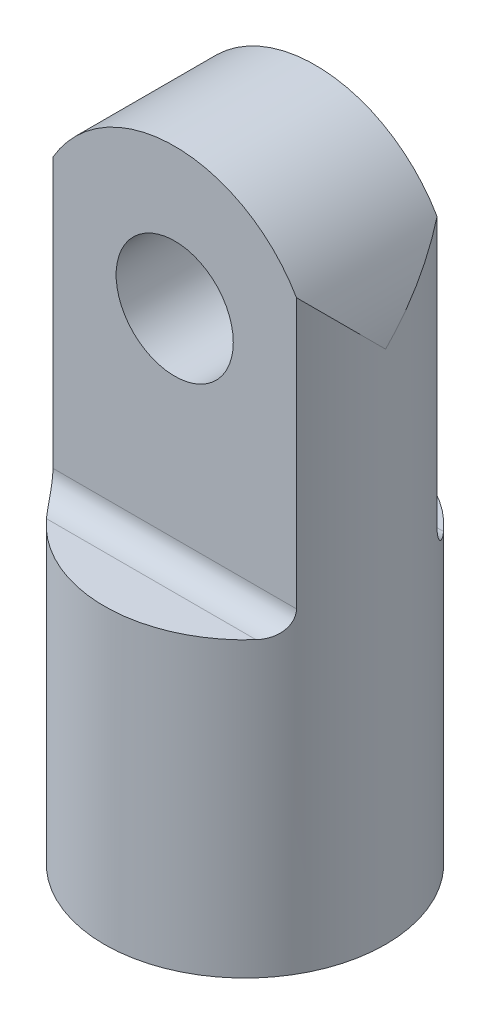
SolidWorks part; units mm, degrees
ref_plane "前视基准面" through (0, 0, 0) normal (0, 0, 1) x (1, 0, 0)
ref_plane "上视基准面" through (0, 0, 0) normal (0, 1, 0) x (1, 0, 0)
ref_plane "右视基准面" through (0, 0, 0) normal (1, 0, 0) x (0, 0, -1)
other "Configuration Table"
sketch "Sketch1" plane through (0, 0, 0) normal (0, 1, 0) x (1, 0, 0)
  circle A0 centre (0, 0) radius 6
  dimension "D1" = 12
extrude "Boss-Extrude1" add sketch "Sketch1" along normal blind 28
sketch "Sketch2" plane through (0, 28, 0) normal (0, 1, 0) x (1, 0, 0)
  line L0 (-7.8504, 0) -> (9.8739, 0) construction
  line L1 (-5.1962, 3) -> (5.1962, 3)
  line L2 (-5.1962, 3) -> (-5.1962, -3)
  line L3 (-5.1962, -3) -> (5.1962, -3)
  line L4 (5.1962, 3) -> (5.1962, -3)
  circle A0 centre (0, 0) radius 6 construction
  circle M6 centre (0, 0) radius 6
  dimension "D1" = 6
extrude "Cut-Extrude1" cut sketch "Sketch2" against normal blind 15.5 contours L1 M6 | L3 M6
sketch "Sketch3" plane through (0, 0, 3) normal (0, 0, 1) x (1, 0, 0)
  line L2 (-5.1962, 28) -> (5.1962, 28) construction
  line L3 (6, 0) -> (6, 28) construction
  line L4 (-6, 28) -> (-6, 0) construction
  circle A0 centre (0, 22) radius 6
  line M2 (5.1962, 28) -> (-5.1962, 28)
  line M10 (-5.1962, 28) -> (-5.1962, 12.5)
  line M11 (5.1962, 12.5) -> (5.1962, 28)
extrude "Cut-Extrude2" cut sketch "Sketch3" against normal through all contours A0 M2 M10 | A0 M11 M2
sketch "Sketch4" plane through (0, 0, 3) normal (0, 0, 1) x (1, 0, 0)
  circle A0 centre (0, 22) radius 2.5
  dimension "D1" = 5
extrude "Cut-Extrude3" cut sketch "Sketch4" against normal through all
fillet "Fillet1" radius 1 2 edges at (0, 12.5, -3) (0, 12.5, 3)
sketch "Sketch6" plane through (0, 0, 3) normal (0, 0, 1) x (1, 0, 0)
  line L1 (-6, 22) -> (-6, 28)
  line L2 (-6, 28) -> (6, 28)
  line L3 (6, 0) -> (6, 28) construction
  line L4 (6, 28) -> (5.1962, 28) construction
  line L5 (6, 28) -> (6, 22)
  circle A1 centre (0, 22) radius 6
  arc A2 (6, 22) -> (-6, 22) centre (0, 22) ccw
  arc M7 (5.1962, 25) -> (-5.1962, 25) centre (0, 22) ccw
  dimension "D1" = 0
extrude "Cut-Extrude4" cut sketch "Sketch6" against normal through all contours A2 L2 L1 M7 | A2 L5 L2 M7
sketch "Sketch7" plane through (0, 0, 0) normal (0, -1, 0) x (1, 0, 0)
  circle A0 centre (0, 0) radius 2.5
  dimension "D1" = 5
extrude "Cut-Extrude5" cut sketch "Sketch7" against normal blind 10
